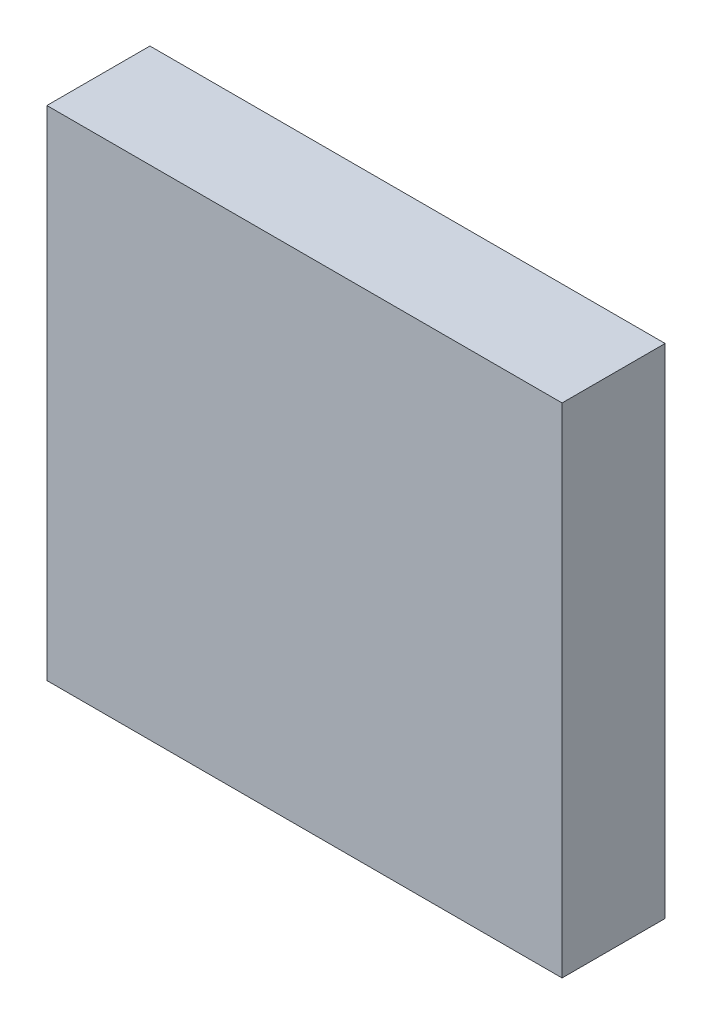
SolidWorks part; units mm, degrees
ref_plane "Спереди" through (0, 0, 0) normal (0, 0, 1) x (1, 0, 0)
ref_plane "Сверху" through (0, 0, 0) normal (0, 1, 0) x (1, 0, 0)
ref_plane "Справа" through (0, 0, 0) normal (1, 0, 0) x (0, 0, -1)
other "Configuration Table"
ref_plane "Плоскость1" through (0, 0, 6) normal (0, 0, 1) x (1, 0, 0)
sketch "Эскиз1" plane through (0, 0, 6) normal (0, 0, 1) x (1, 0, 0)
  line L1 (-30, 42) -> (30, 42)
  line L2 (-30, 42) -> (-30, 100)
  line L3 (-30, 100) -> (30, 100)
  line L4 (30, 42) -> (30, 100)
extrude "Reserved_60x12_insertion_cross_section_1" add sketch "Эскиз1" along normal blind 12
